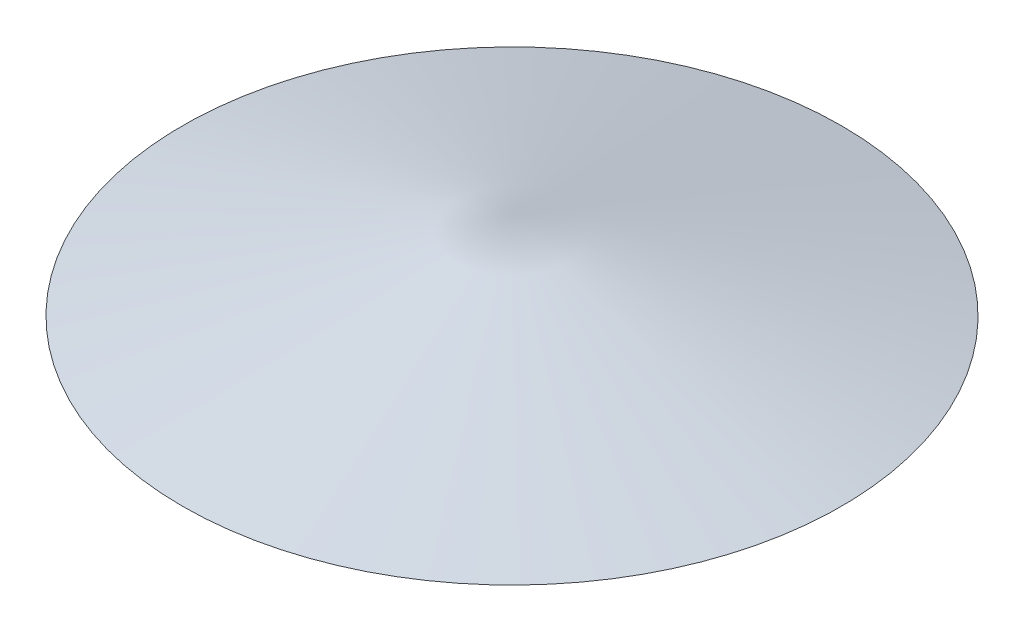
SolidWorks part; units mm, degrees
ref_plane "Plano frontal" through (0, 0, 0) normal (0, 0, 1) x (1, 0, 0)
ref_plane "Plano superior" through (0, 0, 0) normal (0, 1, 0) x (1, 0, 0)
ref_plane "Plano direito" through (0, 0, 0) normal (1, 0, 0) x (0, 0, -1)
sketch "Esboço1" plane through (0, 0, 0) normal (0, 0, 1) x (1, 0, 0)
  line L0 (0, 0) -> (0, 200)
  line L1 (0, 200) -> (746.4102, 0)
  line L2 (746.4102, 0) -> (0, 0)
  dimension "D1" = 75
  dimension "D2" = 200
revolve "Revolução1" add sketch "Esboço1" angle 360 about L0
